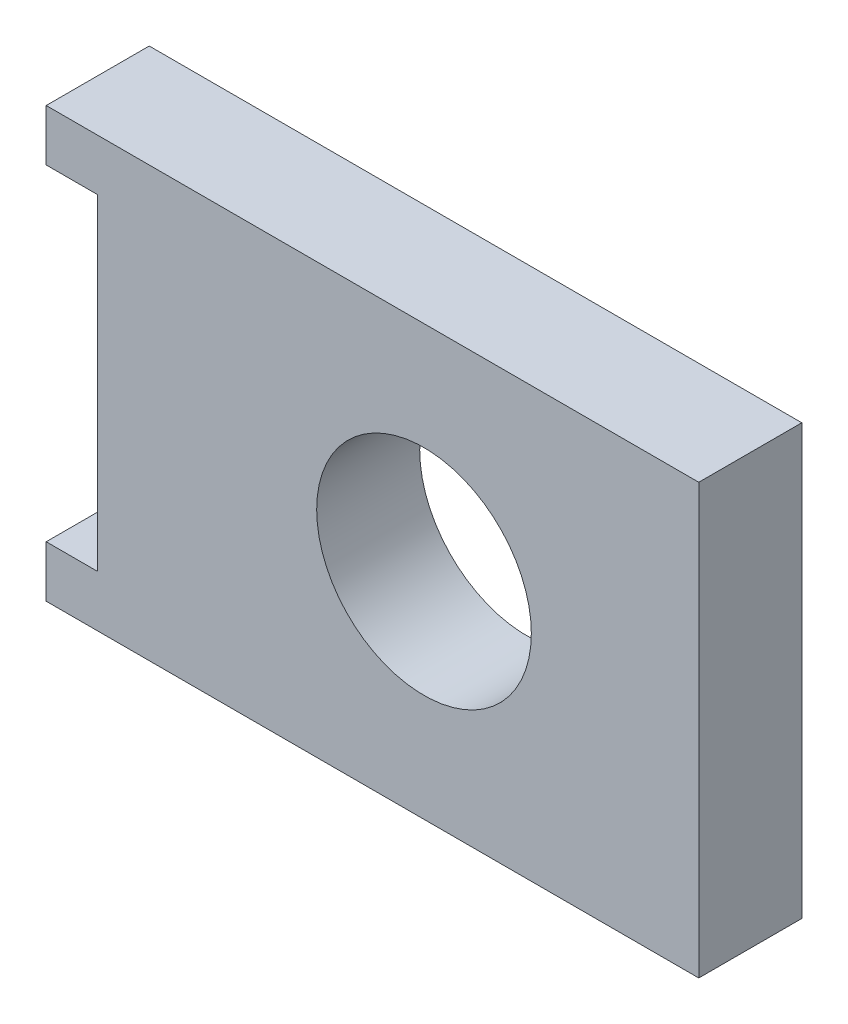
SolidWorks part; units mm, degrees
material "Brass"
ref_plane "Front Plane" through (0, 0, 0) normal (0, 0, 1) x (1, 0, 0)
ref_plane "Top Plane" through (0, 0, 0) normal (0, 1, 0) x (1, 0, 0)
ref_plane "Right Plane" through (0, 0, 0) normal (1, 0, 0) x (0, 0, -1)
sketch "Sketch1" plane through (0, 0, 0) normal (0, 0, 1) x (1, 0, 0)
  line L0 (0, 0) -> (-13544.8714, 0) construction
  line L1 (0, 0) -> (0, -13544.8714) construction
  line L2 (-22, 9.5) -> (-19, 9.5)
  line L3 (-22, 12.5) -> (16, 12.5)
  line L4 (-22, 12.5) -> (-22, 9.5)
  line L5 (-22, -12.5) -> (16, -12.5)
  line L6 (16, 12.5) -> (16, -12.5)
  line L7 (-3, -12.5) -> (-3, 12.5) construction
  line L8 (-22, 0) -> (16, 0) construction
  line L9 (-19, 9.5) -> (-19, -9.5)
  line L10 (-19, -9.5) -> (-22, -9.5)
  line L11 (-22, -9.5) -> (-22, -12.5)
  circle A0 centre (0, 0) radius 6.25
  point P7 (-3, 0)
  dimension "D1" = 12.5
  dimension "D2" = 16
  dimension "D3" = 38
  dimension "D4" = 25
  dimension "D5" = 3
  dimension "D6" = 3
extrude "Boss-Extrude1" add sketch "Sketch1" along normal blind 6
